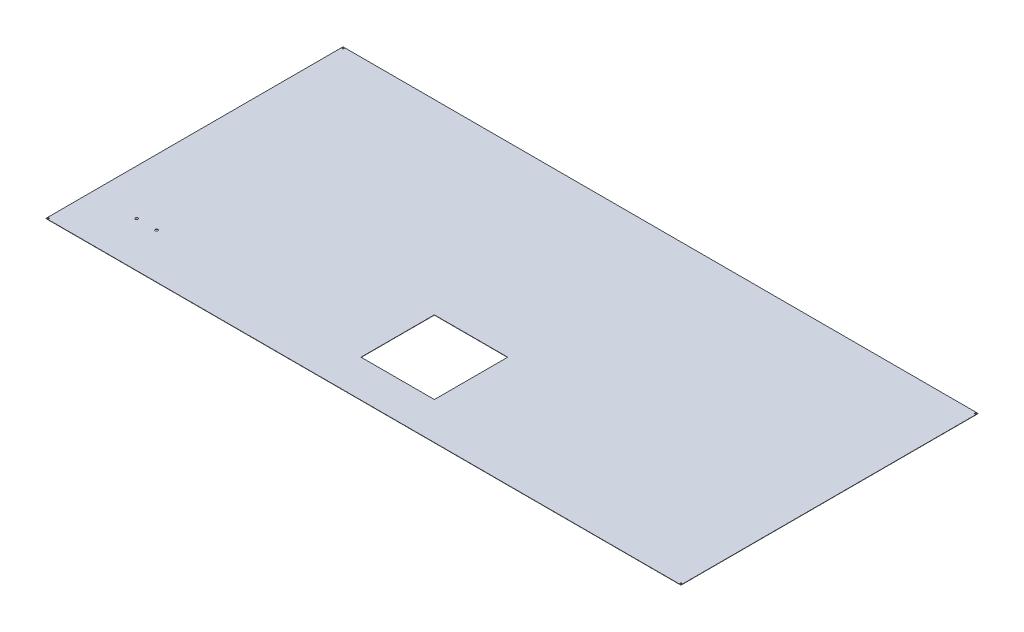
SolidWorks part; units mm, degrees
ref_plane "Front Plane" through (0, 0, 0) normal (0, 0, 1) x (1, 0, 0)
ref_plane "Top Plane" through (0, 0, 0) normal (0, 1, 0) x (1, 0, 0)
ref_plane "Right Plane" through (0, 0, 0) normal (1, 0, 0) x (0, 0, -1)
sketch "Sketch1" plane through (0, 0, 0) normal (0, 1, 0) x (1, 0, 0)
  line L1 (1902, 1012.5) -> (690, 1012.5)
  line L2 (1902, 1012.5) -> (1902, 1579.5)
  line L3 (1902, 1579.5) -> (690, 1579.5)
  line L4 (690, 1012.5) -> (690, 1579.5)
  line L5 (1902, 1012.5) -> (690, 1579.5) construction
  line L6 (1902, 1579.5) -> (690, 1012.5) construction
  point P0 (1296, 1296)
  dimension "D1" = 1212
  dimension "D2" = 567
extrude "Boss-Extrude1" add sketch "Sketch1" along normal blind 0.5
sketch "Sketch2" plane through (0, 0.5, 0) normal (0, 1, 0) x (1, 0, 0)
  line L0 (692, 1577.5) -> (692, 1014.5)
  line L1 (692, 1014.5) -> (1900, 1014.5)
  line L2 (1900, 1014.5) -> (1900, 1577.5)
  line L3 (1900, 1577.5) -> (692, 1577.5)
  line L4 (690, 1579.5) -> (690, 1012.5)
  line L5 (690, 1012.5) -> (1902, 1012.5)
  line L6 (1902, 1012.5) -> (1902, 1579.5)
  line L7 (1902, 1579.5) -> (690, 1579.5)
  line L8 (690, 1579.5) -> (690, 1012.5)
  line L9 (690, 1012.5) -> (1902, 1012.5)
  line L10 (1902, 1012.5) -> (1902, 1579.5)
  line L11 (1902, 1579.5) -> (690, 1579.5)
  point P2 (692, 1577.5)
  point P4 (692, 1014.5)
  point P6 (1900, 1014.5)
  point P7 (1900, 1577.5)
  dimension "D1" = 0
  dimension "D2" = 2
hole_wizard "CSK for M1.6 Countersunk Flat Head Screw1" positions "Sketch2" profile "Sketch3" countersink size "M1.6" standard "ISO"
sketch "Sketch3" plane through (1900, 0.5, -1577.5) normal (1, 0, 0) x (0, 0, 1)
  line L0 (0, 0) -> (0, 30.5408)
  line L1 (0, 30.5408) -> (0.9, 30)
  line L2 (0.9, 30) -> (0.9, 0.9)
  line L3 (0.9, 0.9) -> (1.8, 0)
  line L5 (1.8, 0) -> (0, 0)
  line L6 (-0.9, 0.9) -> (-1.8, 0) construction
  line L10 (0, 30.5408) -> (-0.9, 30) construction
  line L11 (0, -6.35) -> (0, 107.95) construction
  dimension "Hole Dia." = 1.8
  dimension "Hole Depth" = 30
  dimension "Near C'Sink Dia." = 3.6
  dimension "Near C'Sink Angle" = 90
  dimension "Drill Angle" = 118
sketch "Sketch4" plane through (0, 0.5, 0) normal (0, 1, 0) x (1, 0, 0)
  line L1 (1906, 1008.5) -> (686, 1008.5) construction
  line L2 (696, 1573.5) -> (696, 1018.5) construction
  circle A0 centre (777, 1098.5) radius 2.5
  circle A2 centre (815, 1098.5) radius 2.5
  dimension "D1" = 5
  dimension "D4" = 5
  dimension "D2" = 81
  dimension "D3" = 90
  dimension "D5" = 90
  dimension "D6" = 119
extrude "Cut-Extrude1" cut sketch "Sketch4" against normal blind 3
sketch "Sketch5" plane through (0, 0.5, 0) normal (0, 1, 0) x (1, 0, 0)
  line L1 (1220.2436, 1223.58) -> (1360.2436, 1223.58)
  line L2 (1220.2436, 1223.58) -> (1220.2436, 1083.58)
  line L3 (1220.2436, 1083.58) -> (1360.2436, 1083.58)
  line L4 (1360.2436, 1223.58) -> (1360.2436, 1083.58)
extrude "Cut-Extrude2" cut sketch "Sketch5" against normal blind 7
